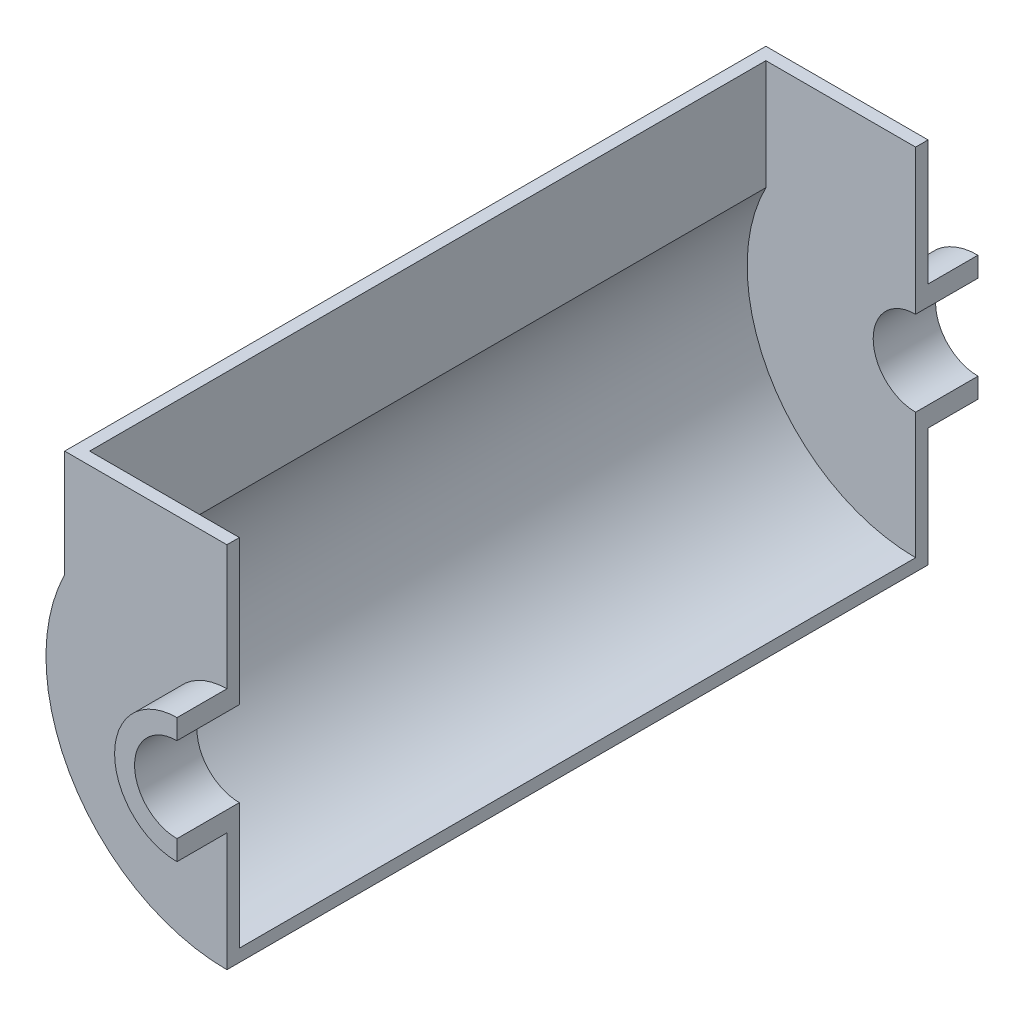
SolidWorks part; units mm, degrees
ref_plane "Front Plane" through (0, 0, 0) normal (0, 0, 1) x (1, 0, 0)
ref_plane "Top Plane" through (0, 0, 0) normal (0, 1, 0) x (1, 0, 0)
ref_plane "Right Plane" through (0, 0, 0) normal (1, 0, 0) x (0, 0, -1)
sketch "Sketch1" plane through (0, 0, 0) normal (0, 0, 1) x (1, 0, 0)
  line L0 (0, 25) -> (0, 17)
  line L1 (0, -17) -> (0, -25)
  arc A0 (0, 25) -> (0, -25) centre (0, 0) ccw
  arc A1 (0, 17) -> (0, -17) centre (0, 0) ccw
  dimension "D1" = 50
  dimension "D2" = 34
extrude "Boss-Extrude1" add sketch "Sketch1" along normal blind 20 and the other way blind 5
sketch "Sketch2" plane through (0, 0, 0) normal (0, 0, 1) x (1, 0, 0)
  line L0 (0, 25) -> (0, 75)
  line L1 (0, 75) -> (-65, 75)
  line L2 (-65, 75) -> (-65, 32.1131)
  line L3 (0, -25) -> (0, -72.5)
  arc A0 (0, 25) -> (0, -25) centre (0, 0) ccw construction
  arc A1 (0, 25) -> (0, -25) centre (0, 0) ccw
  arc A2 (-65, 32.1131) -> (0, -72.5) centre (0, 0) ccw
  dimension "D3" = 72.5
  dimension "D1" = 50
  dimension "D2" = 65
extrude "Boss-Extrude2" add sketch "Sketch2" against normal blind 5
ref_plane "Plane2" through (0, 0, -140.5) normal (0, 0, 1) x (1, 0, 0)
mirror "Mirror4" about plane through (0, 0, -140.5) normal (0, 0, 1) of bodies 102
sketch "Sketch3" plane through (0, 0, -5) normal (0, 0, -1) x (-1, 0, 0)
  line L0 (60, 30.9233) -> (60, 75)
  line L4 (0, -17) -> (0, -72.5)
  line L5 (65, 32.1131) -> (65, 75)
  line L6 (65, 75) -> (0, 75)
  line L7 (0, 75) -> (0, 17)
  line L8 (0, -17) -> (0, -72.5)
  line L9 (65, 32.1131) -> (65, 75)
  line L10 (65, 75) -> (0, 75)
  line L11 (0, 75) -> (0, 17)
  arc A0 (0, -67.5) -> (60, 30.9233) centre (0, 0) ccw
  arc A2 (0, -17) -> (0, 17) centre (0, 0) ccw
  arc A3 (0, -72.5) -> (65, 32.1131) centre (0, 0) ccw
  arc A4 (0, -17) -> (0, 17) centre (0, 0) ccw
  arc A5 (0, -72.5) -> (65, 32.1131) centre (0, 0) ccw
  arc M9 (0, -72.5) -> (65, 32.1131) centre (0, 0) ccw
  line M10 (65, 32.1131) -> (65, 75)
  line M11 (65, 75) -> (0, 75)
  dimension "D1" = 0
  dimension "D2" = 5
extrude "Boss-Extrude3" add sketch "Sketch3" along normal up to surface (271 mm away) contours A0 L8 L0 M9 M10 M11
